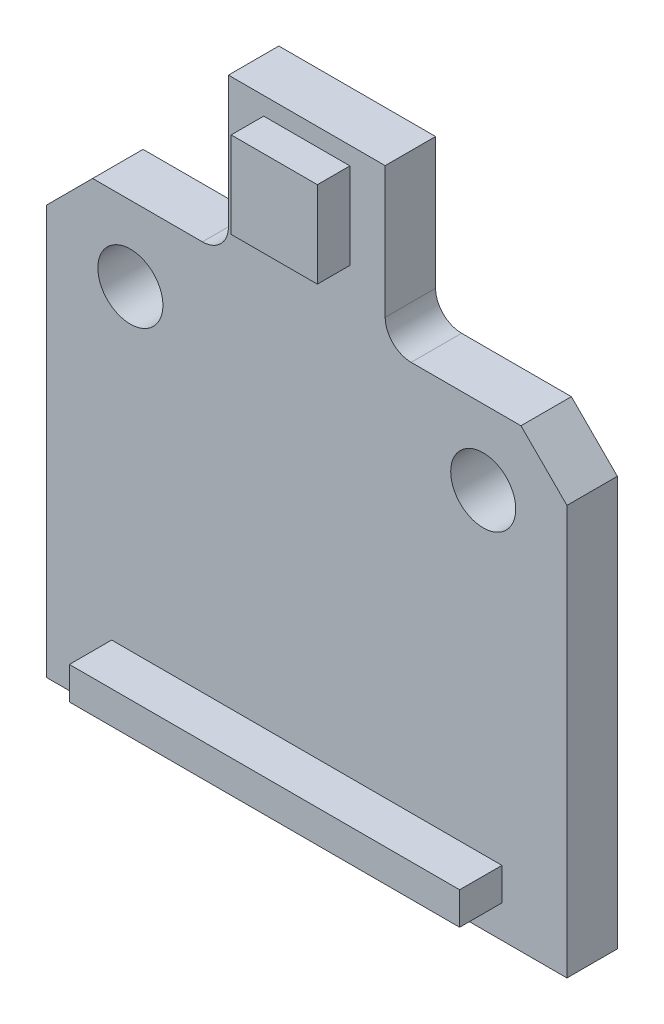
SolidWorks part; units mm, degrees
ref_plane "Front Plane" through (0, 0, 0) normal (0, 0, 1) x (1, 0, 0)
ref_plane "Top Plane" through (0, 0, 0) normal (0, 1, 0) x (1, 0, 0)
ref_plane "Right Plane" through (0, 0, 0) normal (1, 0, 0) x (0, 0, -1)
sketch "Sketch1" plane through (0, 0, 0) normal (0, 0, 1) x (1, 0, 0)
  line L0 (11.21, 14) -> (14.5858, 14)
  line L1 (0, 0) -> (16, 0)
  line L2 (0, 0) -> (0, 12.5858)
  line L3 (1.4142, 14) -> (4.79, 14)
  line L4 (16, 0) -> (16, 12.5858)
  line L5 (0, 0) -> (15.2458, 13.34) construction
  line L6 (0.7542, 13.34) -> (16, 0) construction
  line L8 (5.59, 14.8) -> (5.59, 18.84)
  line L9 (5.59, 18.84) -> (10.41, 18.84)
  line L10 (10.41, 14.8) -> (10.41, 18.84)
  line L11 (5.59, 14) -> (10.41, 18.84) construction
  line L12 (5.59, 18.84) -> (10.41, 14) construction
  line L13 (0, 12.5858) -> (1.4142, 14)
  line L14 (14.5858, 14) -> (16, 12.5858)
  line L15 (2.575, 11.7) -> (0, 11.7) construction
  line L16 (13.425, 11.7) -> (16, 11.7) construction
  arc A0 (11.21, 14) -> (10.41, 14.8) centre (11.21, 14.8) cw
  arc A1 (4.79, 14) -> (5.59, 14.8) centre (4.79, 14.8) ccw
  circle A2 centre (2.575, 11.7) radius 1
  circle A3 centre (13.425, 11.7) radius 1
  point P4 (8, 7)
  point P10 (8, 16.42)
  dimension "D5" = 0.8
  dimension "D10" = 2
  dimension "D1" = 135
  dimension "D2" = 16
  dimension "D3" = 4.82
  dimension "D4" = 4.84
  dimension "D6" = 10.85
  dimension "D7" = 2
  dimension "D8" = 135
  dimension "D9" = 2
  dimension "D11" = 2.3
extrude "Boss-Extrude1" add sketch "Sketch1" along normal blind 1.55
sketch "Sketch2" plane through (0, 0, 1.55) normal (0, 0, 1) x (1, 0, 0)
  line L0 (6.675, 16.3356) -> (5.59, 16.3356) construction
  line L1 (6.675, 18.29) -> (9.325, 18.29)
  line L2 (6.675, 18.29) -> (6.675, 15.64)
  line L3 (6.675, 15.64) -> (9.325, 15.64)
  line L4 (9.325, 18.29) -> (9.325, 15.64)
  line L5 (6.675, 18.29) -> (9.325, 15.64) construction
  line L6 (6.675, 15.64) -> (9.325, 18.29) construction
  line L7 (5.59, 18.84) -> (5.59, 14.8) construction
  line L8 (10.41, 16.1273) -> (9.325, 16.1273) construction
  line L9 (10.41, 14.8) -> (10.41, 18.84) construction
  line L10 (10.41, 18.84) -> (5.59, 18.84) construction
  point P4 (8, 16.965)
  dimension "D1" = 2.65
  dimension "D2" = 0.55
extrude "Boss-Extrude2" add sketch "Sketch2" along normal blind 1
sketch "Sketch3" plane through (0, 0, 1.55) normal (0, 0, 1) x (1, 0, 0)
  line L0 (2, 1.5) -> (0, 1.5) construction
  line L1 (2, 2) -> (14, 2)
  line L2 (2, 2) -> (2, 1)
  line L3 (2, 1) -> (14, 1)
  line L4 (14, 2) -> (14, 1)
  line L5 (2, 2) -> (14, 1) construction
  line L6 (2, 1) -> (14, 2) construction
  line L7 (0, 12.5858) -> (0, 0) construction
  line L8 (14, 1.5) -> (16, 1.5) construction
  line L9 (16, 0) -> (16, 12.5858) construction
  line L10 (0, 0) -> (16, 0) construction
  point P4 (8, 1.5)
  dimension "D1" = 12
  dimension "D2" = 1
  dimension "D3" = 1
extrude "Boss-Extrude3" add sketch "Sketch3" along normal blind 1.3
